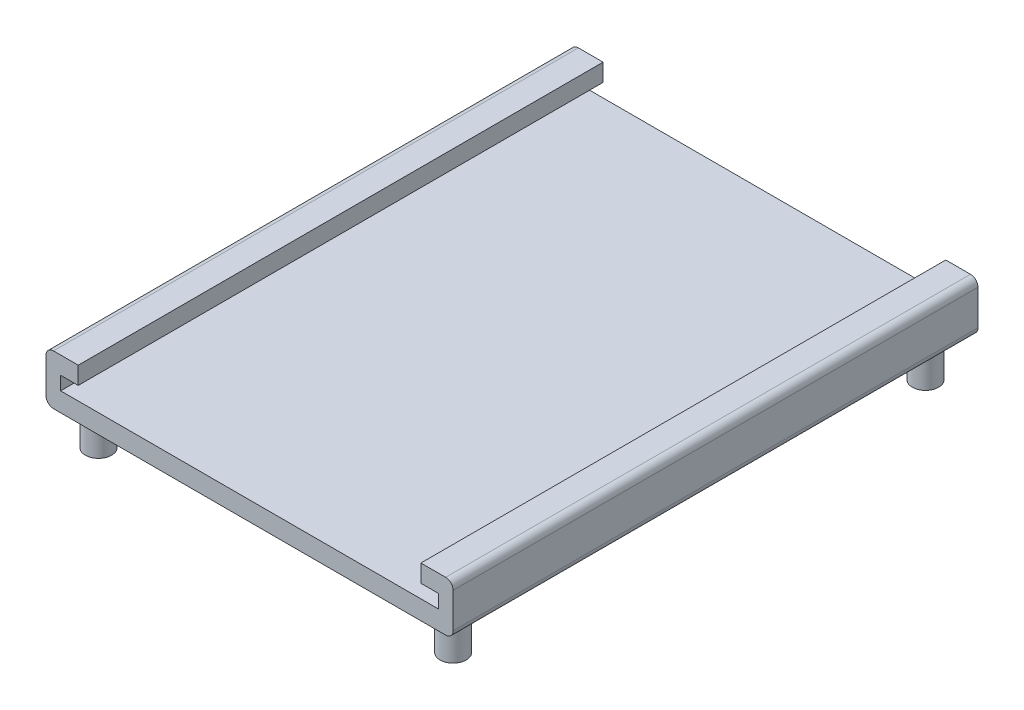
SolidWorks part; units mm, degrees
ref_plane "Front Plane" through (0, 0, 0) normal (0, 0, 1) x (1, 0, 0)
ref_plane "Top Plane" through (0, 0, 0) normal (0, 1, 0) x (1, 0, 0)
ref_plane "Right Plane" through (0, 0, 0) normal (1, 0, 0) x (0, 0, -1)
sketch "Sketch1" plane through (0, 868.1359, 0) normal (0, -1, 0) x (1, 0, 0)
  line L0 (650.181, 1266.5723) -> (650.181, 1336.5723)
  line L1 (650.181, 1336.5723) -> (700.181, 1336.5723)
  line L2 (700.181, 1336.5723) -> (700.181, 1266.5723)
  line L3 (700.181, 1266.5723) -> (650.181, 1266.5723)
extrude "Boss-Extrude1" add sketch "Sketch1" along normal blind 2.54
sketch "Sketch2" plane through (0, 869.7359, 0) normal (0, 1, 0) x (1, 0, 0)
  line L0 (650.181, -1336.5723) -> (700.181, -1336.5723) construction
  line L1 (650.181, -1266.5723) -> (652.331, -1266.5723)
  line L2 (650.181, -1266.5723) -> (650.181, -1336.5723)
  line L3 (650.181, -1336.5723) -> (652.331, -1336.5723)
  line L4 (652.331, -1266.5723) -> (652.331, -1336.5723)
  line L5 (650.181, -1266.5723) -> (652.331, -1336.5723) construction
  line L6 (650.181, -1336.5723) -> (652.331, -1266.5723) construction
  line L8 (700.181, -1266.5723) -> (698.031, -1266.5723)
  line L9 (700.181, -1266.5723) -> (700.181, -1336.5723)
  line L10 (700.181, -1336.5723) -> (698.031, -1336.5723)
  line L11 (698.031, -1266.5723) -> (698.031, -1336.5723)
  line L12 (700.181, -1266.5723) -> (698.031, -1336.5723) construction
  line L13 (700.181, -1336.5723) -> (698.031, -1266.5723) construction
  point P4 (651.256, -1301.5723)
  point P12 (699.106, -1301.5723)
  dimension "D1" = 2.15
  dimension "D2" = 2.15
extrude "Boss-Extrude2" add sketch "Sketch2" along normal blind 2.54 separate body
sketch "Sketch4" plane through (0, 0, 1336.5723) normal (0, 0, 1) x (1, 0, 0)
  line L0 (675.181, 856.3917) -> (675.181, 874.8001) construction
  line L2 (650.181, 865.5959) -> (650.181, 872.2759)
  line L3 (650.181, 865.5959) -> (648.031, 865.5959)
  line L4 (650.181, 872.2759) -> (648.031, 872.2759)
  line L5 (648.031, 865.5959) -> (648.031, 872.2759)
  line L6 (702.331, 865.5959) -> (702.331, 872.2759)
  line L7 (700.181, 872.2759) -> (702.331, 872.2759)
  line L8 (700.181, 865.5959) -> (702.331, 865.5959)
  line L9 (700.181, 865.5959) -> (700.181, 872.2759)
  point P3 (675.181, 865.5959)
  dimension "D1" = 2.15
  dimension "D2" = 25
extrude "Boss-Extrude3" add sketch "Sketch4" against normal up to surface (70 mm away) up to face at (651.256, 871.0059, 1266.5723)
sketch "Sketch6" plane through (0, 0, 1266.5723) normal (0, 0, -1) x (-1, 0, 0)
  line L0 (-675.181, 865.5959) -> (-675.181, 873.7516) construction
  line L1 (-648.031, 865.5959) -> (-702.331, 865.5959) construction
  line L14 (-698.031, 869.7359) -> (-698.031, 868.1359)
  line L15 (-700.181, 868.1359) -> (-650.181, 868.1359) construction
  line L16 (-698.031, 868.1359) -> (-700.381, 868.1359)
  line L17 (-700.381, 868.1359) -> (-700.381, 869.9359)
  line L18 (-700.381, 869.9359) -> (-698.031, 869.9359)
  line L19 (-698.031, 872.2759) -> (-698.031, 869.7359) construction
  line L20 (-698.031, 869.9359) -> (-698.031, 869.7359)
  line L21 (-700.181, 869.7359) -> (-698.031, 869.7359) construction
  line L22 (-700.181, 869.7359) -> (-700.181, 868.1359) construction
  line L23 (-652.331, 869.9359) -> (-652.331, 869.7359)
  line L24 (-649.981, 869.9359) -> (-652.331, 869.9359)
  line L25 (-649.981, 868.1359) -> (-649.981, 869.9359)
  line L26 (-652.331, 868.1359) -> (-649.981, 868.1359)
  line L27 (-652.331, 869.7359) -> (-652.331, 868.1359)
  point P16 (-700.381, 869.0359)
  dimension "D1" = 0.2
  dimension "D2" = 0.2
extrude "Cut-Extrude1" cut sketch "Sketch6" against normal through all
sketch "Sketch8" plane through (0, 865.5959, 0) normal (0, -1, 0) x (1, 0, 0)
  line L0 (675.181, 1336.5723) -> (675.181, 1266.5723) construction
  line L1 (702.331, 1336.5723) -> (648.031, 1336.5723) construction
  line L2 (648.031, 1266.5723) -> (702.331, 1266.5723) construction
  line L3 (702.331, 1301.5723) -> (648.031, 1301.5723) construction
  line L4 (702.331, 1266.5723) -> (702.331, 1336.5723) construction
  line L5 (648.031, 1266.5723) -> (648.031, 1336.5723) construction
  circle A0 centre (651.531, 1333.0723) radius 1.75
  circle A1 centre (698.831, 1333.0723) radius 1.75
  circle A2 centre (698.831, 1270.0723) radius 1.75
  circle A3 centre (651.531, 1270.0723) radius 1.75
  dimension "D1" = 3.5
  dimension "D2" = 3.5
  dimension "D3" = 3.5
extrude "Boss-Extrude4" add sketch "Sketch8" along normal blind 5
fillet "Fillet4" radius 1 4 edges at (648.031, 872.2759, 1301.5723) (648.031, 865.5959, 1301.5723) (702.331, 865.5959, 1301.5723) (702.331, 872.2759, 1301.5723)
